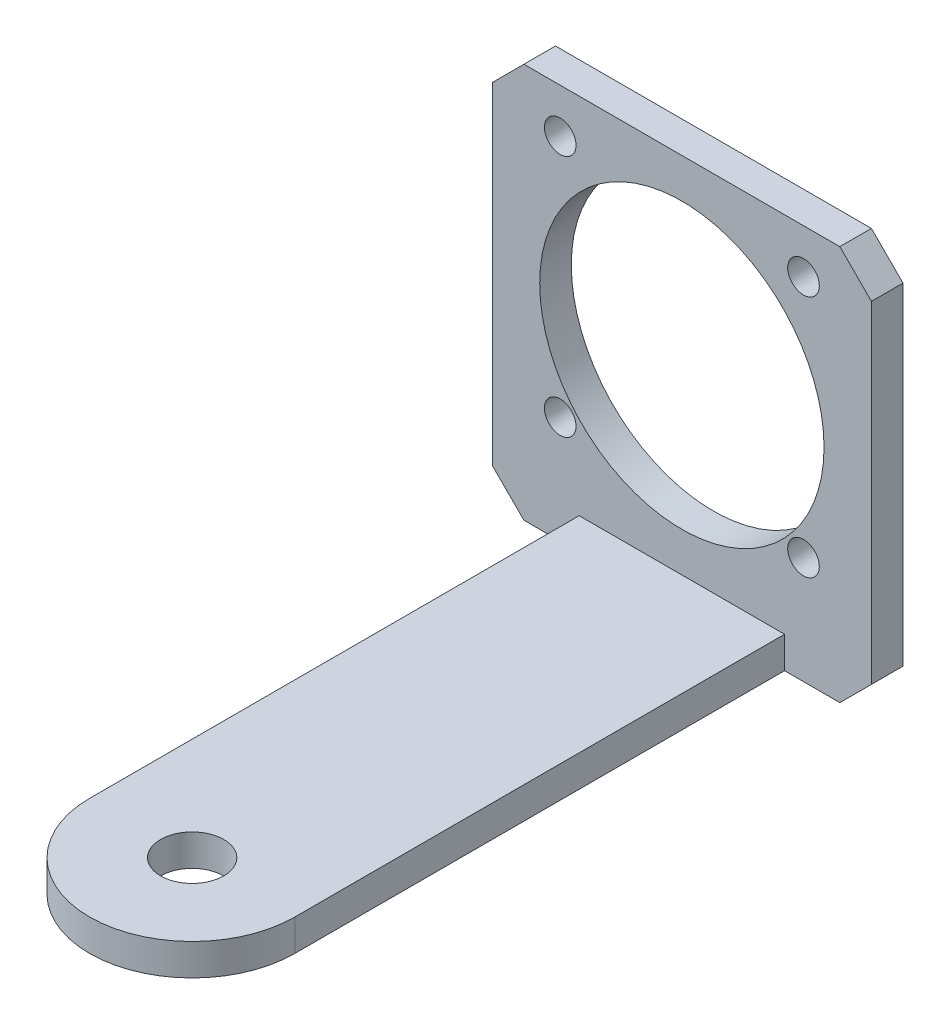
SolidWorks part; units mm, degrees
material "3.0205 (EN-AW 1200)"
ref_plane "前视基准面" through (0, 0, 0) normal (0, 0, 1) x (1, 0, 0)
ref_plane "上视基准面" through (0, 0, 0) normal (0, 1, 0) x (1, 0, 0)
ref_plane "右视基准面" through (0, 0, 0) normal (1, 0, 0) x (0, 0, -1)
sketch "草图1" plane through (0, 0, 0) normal (0, 1, 0) x (1, 0, 0)
  line L1 (5, 0) -> (2.5, 4.3301)
  line L2 (2.5, 4.3301) -> (-2.5, 4.3301)
  line L3 (-2.5, 4.3301) -> (-5, 0)
  line L4 (-5, 0) -> (-2.5, -4.3301)
  line L5 (-2.5, -4.3301) -> (2.5, -4.3301)
  line L6 (5, 0) -> (2.5, -4.3301)
sketch "草图2" plane through (0, 0, 0) normal (0, 1, 0) x (1, 0, 0)
  circle A0 centre (0, 0) radius 6.5
extrude "凸台-拉伸1" add sketch "草图2" along normal blind 2
sketch "草图3" plane through (0, 2, 0) normal (0, 1, 0) x (1, 0, 0)
  circle A0 centre (0, 0) radius 2
extrude "切除-拉伸2" cut sketch "草图3" against normal through all
sketch "草图4" plane through (0, 2, 0) normal (0, 1, 0) x (1, 0, 0)
  line L1 (6.5, 31) -> (3.8991, 31)
  line L3 (-6.5, 0) -> (-6.5, 31)
  line L4 (-6.5, 31) -> (-4.1009, 31)
  line L7 (-6.5, 0) -> (6.5, 0)
  line L8 (6.5, 0) -> (6.5, 31)
  line L11 (-4.1009, 31) -> (3.8991, 31)
  circle A0 centre (0, 0) radius 6.5 construction
  circle A1 centre (0, 0) radius 6.5
extrude "凸台-拉伸2" add sketch "草图4" against normal blind 2
sketch "草图6" plane through (0, 0, -31) normal (0, 0, -1) x (-1, 0, 0)
  line L5 (-15.5564, 5.1908) -> (-3.328, -1.1893)
sketch "草图18" plane through (0, 0, 0) normal (0, -1, 0) x (1, 0, 0)
  circle A0 centre (0, 0) radius 2.5328
sketch "草图20" plane through (0, 0, 0) normal (1, 0, 0) x (0, 0, -1)
  line L0 (0, 2) -> (0, 3)
  circle A0 centre (0, 3) radius 1.5
sketch "草图21" plane through (0, 0, -31) normal (0, 0, -1) x (-1, 0, 0)
  line L0 (0, 0) -> (12, 0)
  line L1 (12, 0) -> (12, 25)
  line L2 (12, 25) -> (-12, 25)
  line L3 (-12, 25) -> (-12, 0)
  line L4 (-12, 0) -> (0, 0)
extrude "凸台-拉伸3" add sketch "草图21" along normal blind 2
sketch "草图22" plane through (0, 0, -31) normal (0, 0, 1) x (1, 0, 0)
  line L0 (-6.5, 2) -> (-12, 2)
  line L1 (-12, 0) -> (-12, 25) construction
  line L2 (0, 2) -> (0, 25)
  line L3 (-6.5, 2) -> (6.5, 2) construction
  line L4 (-12, 25) -> (12, 25) construction
  line L5 (0, 13.5) -> (7.7, 13.5)
  line L6 (7.7, 13.5) -> (7.7, 22.2)
  line L7 (7.7, 22.2) -> (-7.7, 22.2)
  line L8 (-7.7, 22.2) -> (-7.7, 6.8)
  line L9 (-7.7, 6.8) -> (7.7, 6.8)
  circle A0 centre (0, 13.5) radius 9
  circle A1 centre (7.7, 22.2) radius 1
  circle A2 centre (-7.7, 22.2) radius 1
  circle A3 centre (-7.7, 6.8) radius 1
  circle A4 centre (7.7, 6.8) radius 1
extrude "切除-拉伸4" cut sketch "草图22" against normal blind 2 contours A0 | A3 | A4 | A1 | A2
chamfer "倒角1" distance 2 4 edges at (-12, 0, -32) (12, 0, -32) (12, 25, -32) (-12, 25, -32)
